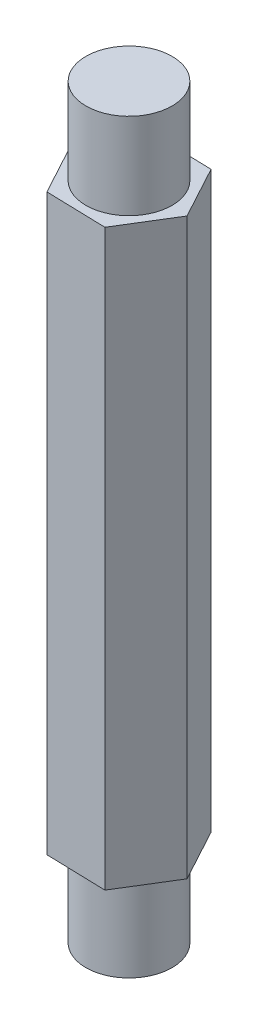
SolidWorks part; units mm, degrees
material "Brass"
ref_plane "Front Plane" through (0, 0, 0) normal (0, 0, 1) x (1, 0, 0)
ref_plane "Top Plane" through (0, 0, 0) normal (0, 1, 0) x (1, 0, 0)
ref_plane "Right Plane" through (0, 0, 0) normal (1, 0, 0) x (0, 0, -1)
sketch "Sketch1" plane through (0, 0, 0) normal (0, 1, 0) x (1, 0, 0)
  circle A0 centre (0, 0) radius 1.5
  dimension "D1" = 3
extrude "Boss-Extrude1" add sketch "Sketch1" along normal blind 3
sketch "Sketch2" plane through (0, 3, 0) normal (0, 1, 0) x (1, 0, 0)
  line L0 (0, 0) -> (-1.5, 0) construction
  line L1 (-0.9892, 1.828) -> (-2.0777, 0.0574)
  line L2 (-2.0777, 0.0574) -> (-1.0885, -1.7706)
  line L3 (-1.0885, -1.7706) -> (0.9892, -1.828)
  line L4 (0.9892, -1.828) -> (2.0777, -0.0574)
  line L5 (2.0777, -0.0574) -> (1.0885, 1.7706)
  line L6 (1.0885, 1.7706) -> (-0.9892, 1.828)
  circle A0 centre (0, 0) radius 1.8 construction
  circle A1 centre (0, 0) radius 1.5 construction
  dimension "D2" = 178.418
  dimension "D1" = 1.8
extrude "Boss-Extrude2" add sketch "Sketch2" along normal blind 20
sketch "Sketch3" plane through (0, 23, 0) normal (0, 1, 0) x (1, 0, 0)
  circle A0 centre (0, 0) radius 1.5
  dimension "D1" = 3
extrude "Boss-Extrude3" add sketch "Sketch3" along normal blind 3
